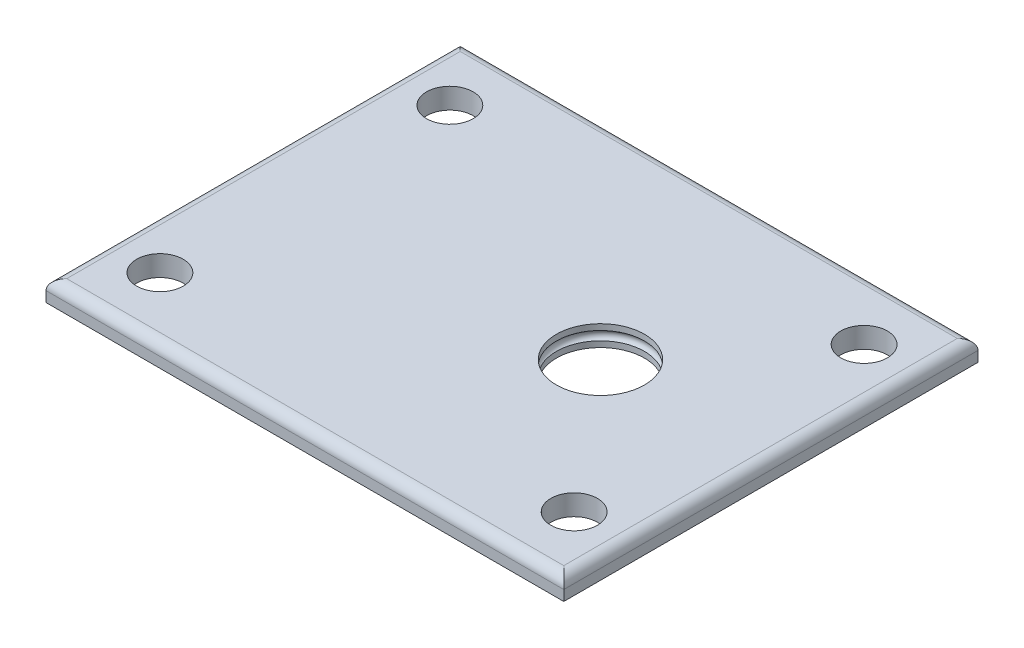
SolidWorks part; units mm, degrees
ref_plane "Front Plane" through (0, 0, 0) normal (0, 0, 1) x (1, 0, 0)
ref_plane "Top Plane" through (0, 0, 0) normal (0, 1, 0) x (1, 0, 0)
ref_plane "Right Plane" through (0, 0, 0) normal (1, 0, 0) x (0, 0, -1)
sketch "Sketch2" plane through (0, 0, 0) normal (0, 1, 0) x (1, 0, 0)
  line L0 (40, 0) -> (40, -28) construction
  line L1 (0, 0) -> (40, 0) construction
  line L2 (-5, 6) -> (45, 6)
  line L3 (-5, 6) -> (-5, -34)
  line L4 (-5, -34) -> (45, -34)
  line L5 (45, 6) -> (45, -34)
  circle A0 centre (0, 0) radius 2.25
  circle A1 centre (40, 0) radius 2.25
  circle A2 centre (0, -28) radius 2.25
  circle A3 centre (40, -28) radius 2.25
  point P8 (40, -14)
  point P14 (45, -14)
  point P15 (20, 0)
  point P16 (20, 6)
  dimension "D1" = 4.5
  dimension "D2" = 28
  dimension "D3" = 40
  dimension "D4" = 50
  dimension "D5" = 40
extrude "Boss-Extrude1" add sketch "Sketch2" along normal blind 2
sketch "Sketch3" [suppressed] plane through (0, 2, 0) normal (0, 1, 0) x (1, 0, 0)
  line L0 (45, -34) -> (45, 6) construction
  circle A0 centre (28.54, -14) radius 15.25
  circle A3 centre (40, 0) radius 2.25 construction
  circle A4 centre (28.54, -14) radius 12.8
  point P7 (45, -14)
  dimension "D1" = 30.5
  dimension "D2" = 25.6
  dimension "D3" = 11.46
extrude "Cut-Extrude2" [suppressed] cut sketch "Sketch3" against normal blind 1
sketch "Sketch4" plane through (0, 2, 0) normal (0, 1, 0) x (1, 0, 0)
  line L0 (45, -34) -> (45, 6) construction
  circle A0 centre (28.54, -14) radius 4.25
  circle A1 centre (40, 0) radius 2.25 construction
  point P6 (45, -14)
  dimension "D1" = 8.5
  dimension "D2" = 11.46
extrude "Cut-Extrude3" cut sketch "Sketch4" against normal up to next
ref_plane "Plane1" through (0, 0, 14) normal (0, 0, -1) x (-1, 0, 0)
sketch "Sketch7" plane through (0, 0, 14) normal (0, 0, -1) x (-1, 0, 0)
  line L0 (-28.54, 2) -> (-28.54, 0) construction
  line L1 (-45, 2) -> (5, 2) construction
  line L2 (-45, 0) -> (5, 0) construction
  line L3 (-45, 2) -> (-45, 0) construction
  line L4 (-24.54, 1.5) -> (-24.54, 0.5)
  arc A0 (-24.54, 1.5) -> (-24.54, 0.5) centre (-24.54, 1) cw
  point P11 (-24.54, 0.1998)
  point P12 (-24.54, 1.7263)
  point P13 (-24.6698, 1.8569)
  point P14 (-24.678, 1.8977)
  point P15 (-24.54, 1)
  point P16 (-28.54, 1)
  point P17 (-24.54, 1.393)
  point P18 (0, 0)
  dimension "D2" = 4
  dimension "D3" = 0.5
  dimension "D1" = 16.46
revolve "Cut-Revolve1" cut sketch "Sketch7" angle 360 about L0
fillet "Fillet2" radius 1 4 edges at (-5, 2, 14) (20, 2, -6) (45, 2, 14) (20, 2, 34)
